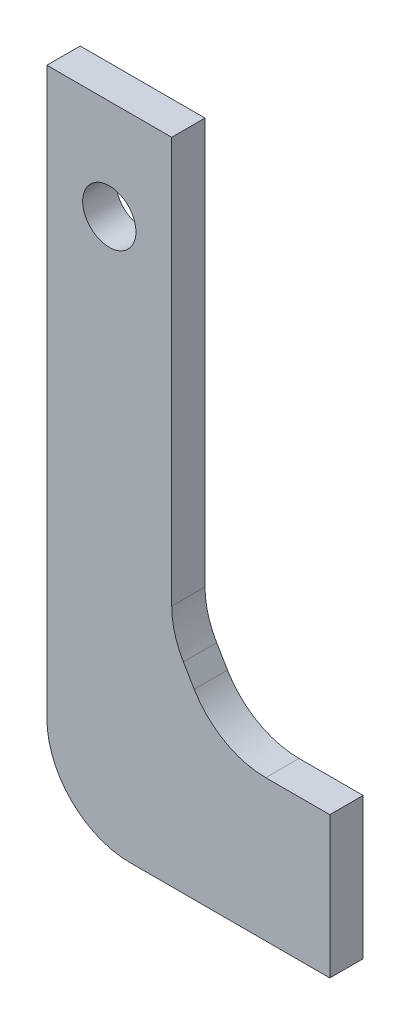
SolidWorks part; units mm, degrees
ref_plane "前视基准面" through (0, 0, 0) normal (0, 0, 1) x (1, 0, 0)
ref_plane "上视基准面" through (0, 0, 0) normal (0, 1, 0) x (1, 0, 0)
ref_plane "右视基准面" through (0, 0, 0) normal (1, 0, 0) x (0, 0, -1)
sketch "草图1" plane through (0, 0, 0) normal (0, 0, 1) x (1, 0, 0)
  line L0 (-13.5877, 1.955) -> (-14.2415, 3.057)
  line L1 (-22.4414, 30.0063) -> (-14.9414, 30.0063)
  line L2 (-22.4414, 30.0063) -> (-22.4414, -3.9937)
  line L4 (-14.9414, 30.0063) -> (-14.9414, 5.6083)
  line L5 (-17.4414, -8.9937) -> (-5.4414, -8.9937)
  line L7 (-9.2876, -0.4937) -> (-5.4414, -0.4937)
  line L8 (-5.4414, -8.9937) -> (-5.4414, -0.4937)
  arc A0 (-13.5877, 1.955) -> (-9.2876, -0.4937) centre (-9.2876, 4.5063) ccw
  arc A1 (-14.2415, 3.057) -> (-14.9414, 5.6083) centre (-9.9414, 5.6083) cw
  arc A2 (-22.4414, -3.9937) -> (-17.4414, -8.9937) centre (-17.4414, -3.9937) ccw
  circle A3 centre (-18.6914, 24.0063) radius 1.6
  dimension "D5" = 5
  dimension "D6" = 5
  dimension "D1" = 6
  dimension "D2" = 3.2
  dimension "D3" = 7.5
  dimension "D4" = 8.5
extrude "凸台-拉伸2" add sketch "草图1" along normal blind 2 contours L4 A1 L0 A0 L7 L8 L5 A2 L2 L1 | A3
